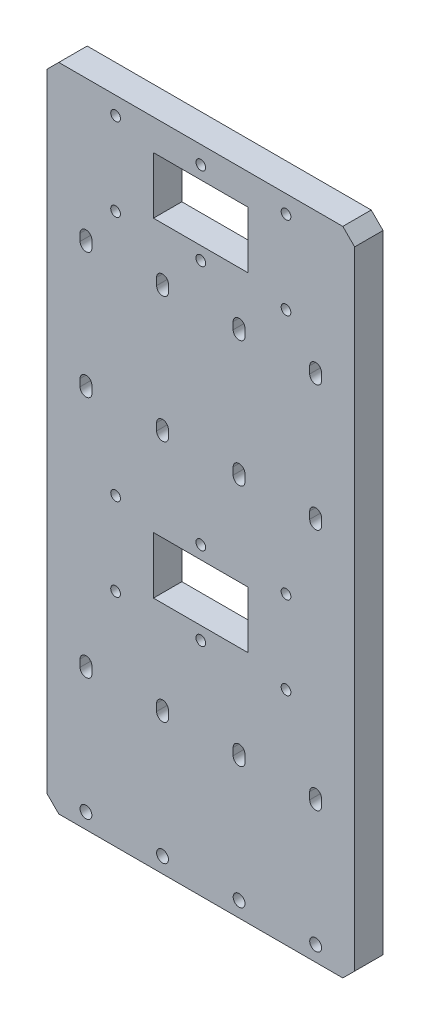
SolidWorks part; units mm, degrees
material "Beech"
ref_plane "Front Plane" through (0, 0, 0) normal (0, 0, 1) x (1, 0, 0)
ref_plane "Top Plane" through (0, 0, 0) normal (0, 1, 0) x (1, 0, 0)
ref_plane "Right Plane" through (0, 0, 0) normal (1, 0, 0) x (0, 0, -1)
sketch "Model" plane through (0, 0, 0) normal (0, 0, 1) x (1, 0, 0)
  line L0 (5, 275) -> (0, 270)
  line L1 (125, 275) -> (5, 275)
  line L2 (130, 270) -> (125, 275)
  line L3 (125, 0) -> (130, 5)
  line L4 (0, 5) -> (5, 0)
  line L5 (85, 99) -> (45, 99)
  line L6 (85, 123) -> (85, 99)
  line L7 (45, 123) -> (85, 123)
  line L8 (45, 99) -> (45, 123)
  line L9 (13.99, 163.82) -> (13.99, 160.82)
  line L10 (18.99, 160.82) -> (18.99, 163.82)
  line L11 (46.33, 163.82) -> (46.33, 160.82)
  line L12 (51.33, 160.82) -> (51.33, 163.82)
  line L13 (78.67, 163.82) -> (78.67, 160.82)
  line L14 (83.67, 160.82) -> (83.67, 163.82)
  line L15 (111.01, 163.82) -> (111.01, 160.82)
  line L16 (116.01, 160.82) -> (116.01, 163.82)
  line L17 (13.99, 217) -> (13.99, 214)
  line L18 (18.99, 214) -> (18.99, 217)
  line L19 (51.33, 214) -> (51.33, 217)
  line L20 (46.33, 217) -> (46.33, 214)
  line L21 (83.67, 214) -> (83.67, 217)
  line L22 (78.67, 217) -> (78.67, 214)
  line L23 (116.01, 214) -> (116.01, 217)
  line L24 (111.01, 217) -> (111.01, 214)
  line L25 (18.99, 58.18) -> (18.99, 61.18)
  line L26 (13.99, 61.18) -> (13.99, 58.18)
  line L27 (51.33, 58.18) -> (51.33, 61.18)
  line L28 (46.33, 61.18) -> (46.33, 58.18)
  line L29 (83.67, 58.18) -> (83.67, 61.18)
  line L30 (78.67, 61.18) -> (78.67, 58.18)
  line L31 (116.01, 58.18) -> (116.01, 61.18)
  line L32 (111.01, 61.18) -> (111.01, 58.18)
  line L33 (85, 262) -> (45, 262)
  line L34 (45, 262) -> (45, 238)
  line L35 (45, 238) -> (85, 238)
  line L36 (85, 238) -> (85, 262)
  line L37 (0, 270) -> (0, 5)
  line L38 (130, 5) -> (130, 270)
  line L39 (5, 0) -> (125, 0)
  line L40 (29, 232.5) -> (101, 232.5) construction
  line L41 (16.49, 6.5) -> (113.51, 6.5) construction
  line L42 (16.49, 6.5) -> (16.49, 61.18) construction
  line L43 (16.49, 61.18) -> (113.51, 61.18) construction
  line L44 (113.51, 6.5) -> (113.51, 61.18) construction
  line L45 (29, 93.5) -> (101, 93.5) construction
  line L46 (29, 93.5) -> (29, 128.5) construction
  line L47 (29, 128.5) -> (101, 128.5) construction
  line L48 (101, 93.5) -> (101, 128.5) construction
  line L49 (101, 232.5) -> (101, 267.5) construction
  line L50 (101, 267.5) -> (29, 267.5) construction
  line L51 (29, 267.5) -> (29, 232.5) construction
  line L52 (16.49, 217) -> (113.51, 217) construction
  line L53 (113.51, 217) -> (113.51, 160.82) construction
  line L54 (113.51, 160.82) -> (16.49, 160.82) construction
  line L55 (16.49, 160.82) -> (16.49, 217) construction
  line L56 (16.49, 214) -> (113.51, 214) construction
  line L57 (16.49, 163.82) -> (113.51, 163.82) construction
  line L58 (16.49, 160.82) -> (16.49, 61.18) construction
  line L59 (48.83, 160.82) -> (48.83, 61.18) construction
  line L60 (48.83, 61.18) -> (48.83, 6.5) construction
  line L61 (81.17, 163.82) -> (81.17, 61.18) construction
  line L62 (81.17, 61.18) -> (81.17, 6.5) construction
  line L63 (113.51, 160.82) -> (113.51, 61.18) construction
  line L64 (16.49, 58.18) -> (113.51, 58.18) construction
  line L65 (48.83, 217) -> (48.83, 160.82) construction
  line L66 (81.17, 217) -> (81.17, 163.82) construction
  line L67 (0, 5) -> (0, 0) construction
  line L68 (5, 0) -> (0, 0) construction
  circle A0 centre (16.49, 6.5) radius 2.5
  circle A1 centre (48.83, 6.5) radius 2.5
  circle A2 centre (81.17, 6.5) radius 2.5
  circle A3 centre (113.51, 6.5) radius 2.5
  circle A4 centre (29, 128.5) radius 2.05
  circle A5 centre (65, 128.5) radius 2.05
  circle A6 centre (101, 128.5) radius 2.05
  circle A7 centre (101, 93.5) radius 2.05
  circle A8 centre (65, 93.5) radius 2.05
  circle A9 centre (29, 93.5) radius 2.05
  circle A10 centre (29, 267.5) radius 2.05
  circle A11 centre (65, 267.5) radius 2.05
  circle A12 centre (101, 267.5) radius 2.05
  circle A13 centre (101, 232.5) radius 2.05
  circle A14 centre (65, 232.5) radius 2.05
  circle A15 centre (29, 232.5) radius 2.05
  arc A16 (13.99, 160.82) -> (18.99, 160.82) centre (16.49, 160.82) ccw
  arc A17 (18.99, 163.82) -> (13.99, 163.82) centre (16.49, 163.82) ccw
  arc A18 (46.33, 160.82) -> (51.33, 160.82) centre (48.83, 160.82) ccw
  arc A19 (51.33, 163.82) -> (46.33, 163.82) centre (48.83, 163.82) ccw
  arc A20 (78.67, 160.82) -> (83.67, 160.82) centre (81.17, 160.82) ccw
  arc A21 (83.67, 163.82) -> (78.67, 163.82) centre (81.17, 163.82) ccw
  arc A22 (111.01, 160.82) -> (116.01, 160.82) centre (113.51, 160.82) ccw
  arc A23 (116.01, 163.82) -> (111.01, 163.82) centre (113.51, 163.82) ccw
  arc A24 (13.99, 214) -> (18.99, 214) centre (16.49, 214) ccw
  arc A25 (18.99, 217) -> (13.99, 217) centre (16.49, 217) ccw
  arc A26 (46.33, 214) -> (51.33, 214) centre (48.83, 214) ccw
  arc A27 (51.33, 217) -> (46.33, 217) centre (48.83, 217) ccw
  arc A28 (78.67, 214) -> (83.67, 214) centre (81.17, 214) ccw
  arc A29 (83.67, 217) -> (78.67, 217) centre (81.17, 217) ccw
  arc A30 (111.01, 214) -> (116.01, 214) centre (113.51, 214) ccw
  arc A31 (116.01, 217) -> (111.01, 217) centre (113.51, 217) ccw
  arc A32 (13.99, 58.18) -> (18.99, 58.18) centre (16.49, 58.18) ccw
  arc A33 (18.99, 61.18) -> (13.99, 61.18) centre (16.49, 61.18) ccw
  arc A34 (46.33, 58.18) -> (51.33, 58.18) centre (48.83, 58.18) ccw
  arc A35 (51.33, 61.18) -> (46.33, 61.18) centre (48.83, 61.18) ccw
  arc A36 (78.67, 58.18) -> (83.67, 58.18) centre (81.17, 58.18) ccw
  arc A37 (83.67, 61.18) -> (78.67, 61.18) centre (81.17, 61.18) ccw
  arc A38 (111.01, 58.18) -> (116.01, 58.18) centre (113.51, 58.18) ccw
  arc A39 (116.01, 61.18) -> (111.01, 61.18) centre (113.51, 61.18) ccw
  point P120 (29, 111)
  dimension "D13" = 4.1
  dimension "D14" = 2.5
  dimension "D15" = 130
  dimension "D1" = 6.5
  dimension "D2" = 61.18
  dimension "D3" = 93.5
  dimension "D4" = 35
  dimension "D5" = 35.32
  dimension "D6" = 53.18
  dimension "D7" = 15.5
  dimension "D8" = 35
  dimension "D9" = 275
  dimension "D10" = 24
  dimension "D11" = 11
  dimension "D12" = 5.5
  dimension "D16" = 16.49
  dimension "D17" = 32.34
  dimension "D18" = 32.34
  dimension "D19" = 32.34
  dimension "D20" = 29
  dimension "D21" = 72
  dimension "D22" = 40
  dimension "D23" = 16
  dimension "D24" = 29
  dimension "D25" = 72
  dimension "D26" = 5
  dimension "D27" = 5
  dimension "D28" = 3
  dimension "D29" = 5
extrude "Boss-Extrude1" add sketch "Model" along normal blind 12
